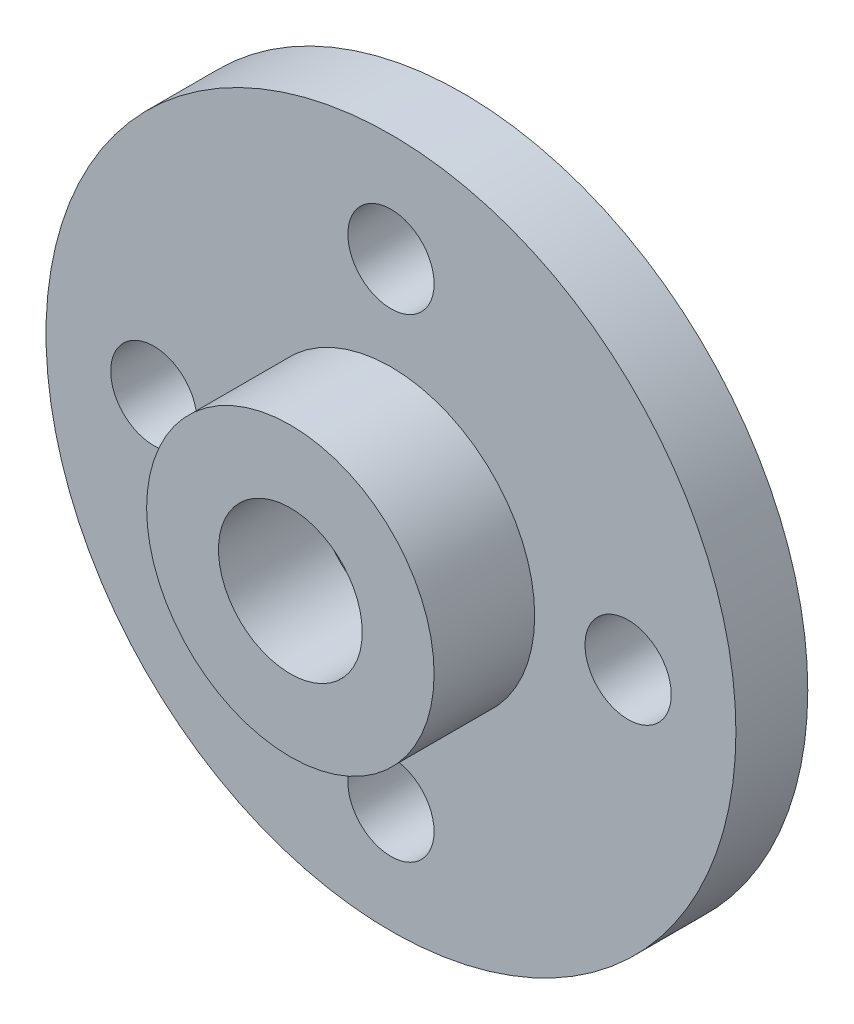
SolidWorks part; units mm, degrees
material "1060 合金"
ref_plane "前视基准面" through (0, 0, 0) normal (0, 0, 1) x (1, 0, 0)
ref_plane "上视基准面" through (0, 0, 0) normal (0, 1, 0) x (1, 0, 0)
ref_plane "右视基准面" through (0, 0, 0) normal (1, 0, 0) x (0, 0, -1)
sketch "草图1" plane through (0, 0, 0) normal (0, 0, 1) x (1, 0, 0)
  circle A0 centre (0, 0) radius 12
  circle A1 centre (0, 0) radius 1.5
  circle A6 centre (0, 0) radius 8.25 construction
  circle A7 centre (0, 8.25) radius 1.5
  circle A8 centre (8.25, 0) radius 1.5
  circle A9 centre (0, -8.25) radius 1.5
  circle A10 centre (-8.25, 0) radius 1.5
  point P16 (0, 0)
  dimension "D1" = 24
  dimension "D2" = 3
  dimension "D3" = 16.5
  dimension "D4" = 3
  dimension "D5" = 4
extrude "凸台-拉伸1" add sketch "草图1" along normal blind 2.5
sketch "草图2" plane through (0, 0, 2.5) normal (0, 0, 1) x (1, 0, 0)
  circle A0 centre (0, 0) radius 5
  circle A1 centre (0, 0) radius 2.5
  dimension "D1" = 10
  dimension "D2" = 5
extrude "凸台-拉伸2" add sketch "草图2" along normal blind 3.5
